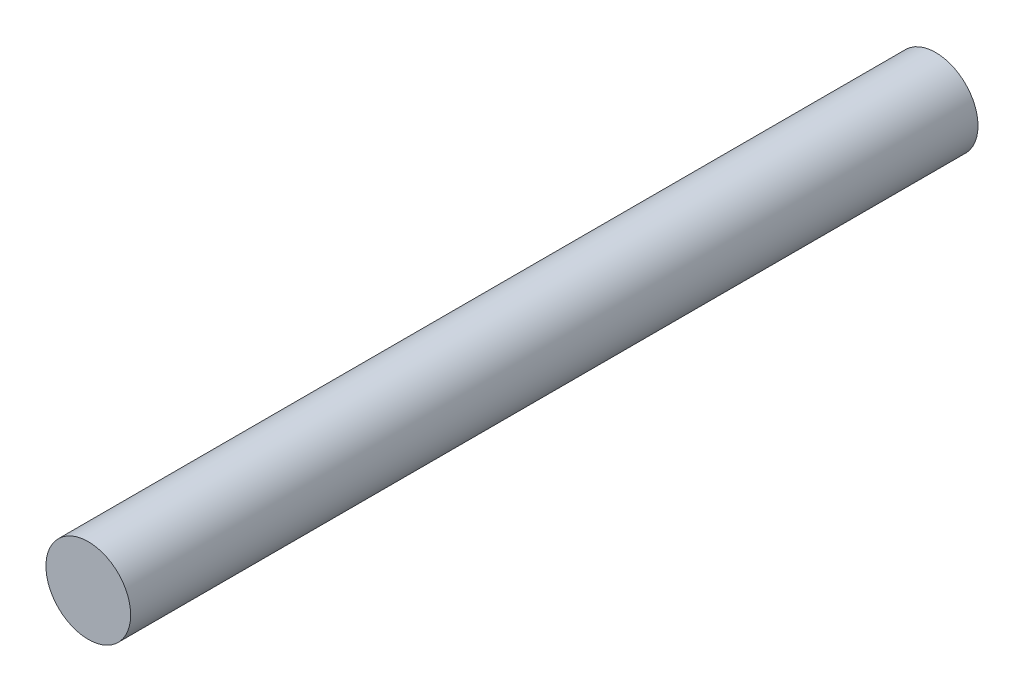
SolidWorks part; units mm, degrees
ref_plane "Front Plane" through (0, 0, 0) normal (0, 0, 1) x (1, 0, 0)
ref_plane "Top Plane" through (0, 0, 0) normal (0, 1, 0) x (1, 0, 0)
ref_plane "Right Plane" through (0, 0, 0) normal (1, 0, 0) x (0, 0, -1)
sketch "Sketch1" plane through (0, 0, 0) normal (0, 0, 1) x (1, 0, 0)
  circle A0 centre (0, 0) radius 5
extrude "Boss-Extrude1" add sketch "Sketch1" along normal blind 100 contours A0
